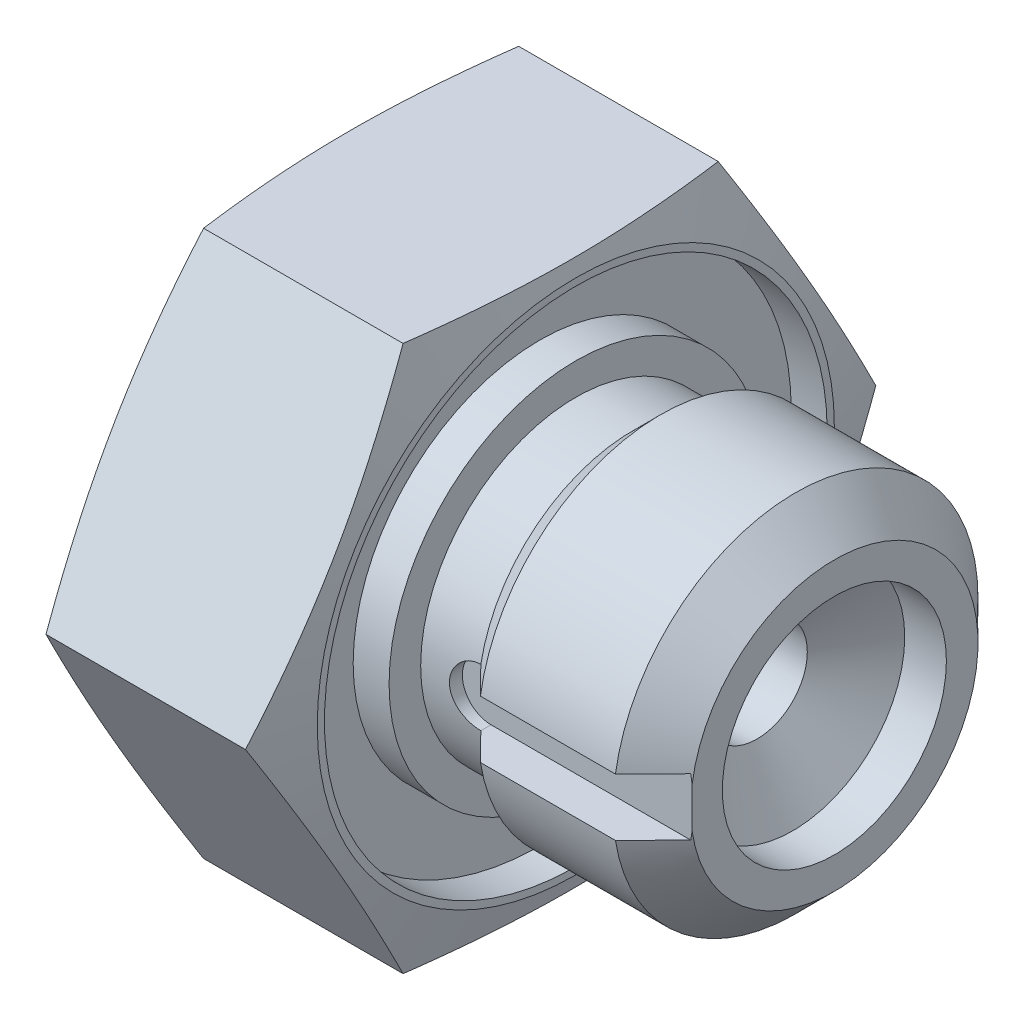
SolidWorks part; units mm, degrees
material "316 S/Steel"
ref_plane "Front Plane" through (0, 0, 0) normal (0, 0, 1) x (1, 0, 0)
ref_plane "Top Plane" through (0, 0, 0) normal (0, 1, 0) x (1, 0, 0)
ref_plane "Right Plane" through (0, 0, 0) normal (1, 0, 0) x (0, 0, -1)
sketch "Sketch1" plane through (0, 0, 0) normal (0, 0, 1) x (1, 0, 0)
  line L0 (0, 3.9) -> (0, 5)
  line L1 (0, 5) -> (-1.35, 6.35)
  line L2 (-1.35, 6.35) -> (-6.05, 6.35)
  line L3 (-6.05, 6.35) -> (-7, 5.4)
  line L4 (-7, 5.4) -> (-9, 5.4)
  line L5 (-9, 5.4) -> (-9, 6.5)
  line L6 (-9, 6.5) -> (-10.25, 6.5)
  line L7 (-10.25, 6.5) -> (-10.25, 8.75)
  line L8 (-10.25, 8.75) -> (-9, 8.75)
  line L9 (-9, 8.75) -> (-9, 9)
  line L10 (-10.6077, 15) -> (-15.3923, 15)
  line L11 (-17, 9) -> (-17, 1.75)
  line L12 (-17, 1.75) -> (-2.6913, 1.75)
  line L13 (-2.6913, 1.75) -> (-1.45, 3.9)
  line L14 (-1.45, 3.9) -> (0, 3.9)
  line L15 (0, 0) -> (-17, 0) construction
  line L16 (-15.3923, 15) -> (-17, 9)
  line L17 (-10.6077, 15) -> (-9, 9)
  dimension "D1" = 17
  dimension "D2" = 3.5
  dimension "D3" = 7.8
  dimension "D4" = 1.45
  dimension "D5" = 60
  dimension "D6" = 12.7
  dimension "D7" = 8
  dimension "D8" = 2
  dimension "D9" = 45
  dimension "D10" = 10.8
  dimension "D11" = 45
  dimension "D12" = 1.25
  dimension "D13" = 13
  dimension "D14" = 17.5
  dimension "D15" = 30
  dimension "D16" = 10
  dimension "D17" = 18
  dimension "D18" = 75
  dimension "D19" = 75
revolve "Revolve1" add sketch "Sketch1" angle 360 about L15
cosmetic thread "Cosmetic Thread1" parameters "D1"=7, "D2"=10.8
sketch "Sketch2" plane through (-17, 0, 0) normal (-1, 0, 0) x (0, 0, 1)
  line L1 (10.9697, 0) -> (5.4848, 9.5)
  line L2 (5.4848, 9.5) -> (-5.4848, 9.5)
  line L3 (-5.4848, 9.5) -> (-10.9697, 0)
  line L4 (-10.9697, 0) -> (-5.4848, -9.5)
  line L5 (-5.4848, -9.5) -> (5.4848, -9.5)
  line L6 (5.4848, -9.5) -> (10.9697, 0)
  circle A0 centre (0, 0) radius 9.5 construction
extrude "Cut-Extrude1" cut sketch "Sketch2" against normal through all flip side to cut
ref_plane "Plane1" through (0, 0, 4.95) normal (0, 0, 1) x (1, 0, 0)
sketch "Sketch3" plane through (0, 0, 4.95) normal (0, 0, 1) x (1, 0, 0)
  line L0 (0, 0) -> (-7.6105, 0) construction
  line L1 (0, 1) -> (-7, 1)
  line L2 (0, 0) -> (0, 1)
  line L3 (-7, 5.4) -> (-7, -5.4) construction
  line L4 (0, -1) -> (-7, -1)
  line L5 (0, -1) -> (0, 0)
  arc A0 (-7, 1) -> (-7, -1) centre (-7, 0) ccw
  dimension "D1" = 2
extrude "Cut-Extrude3" cut sketch "Sketch3" along normal blind 10
